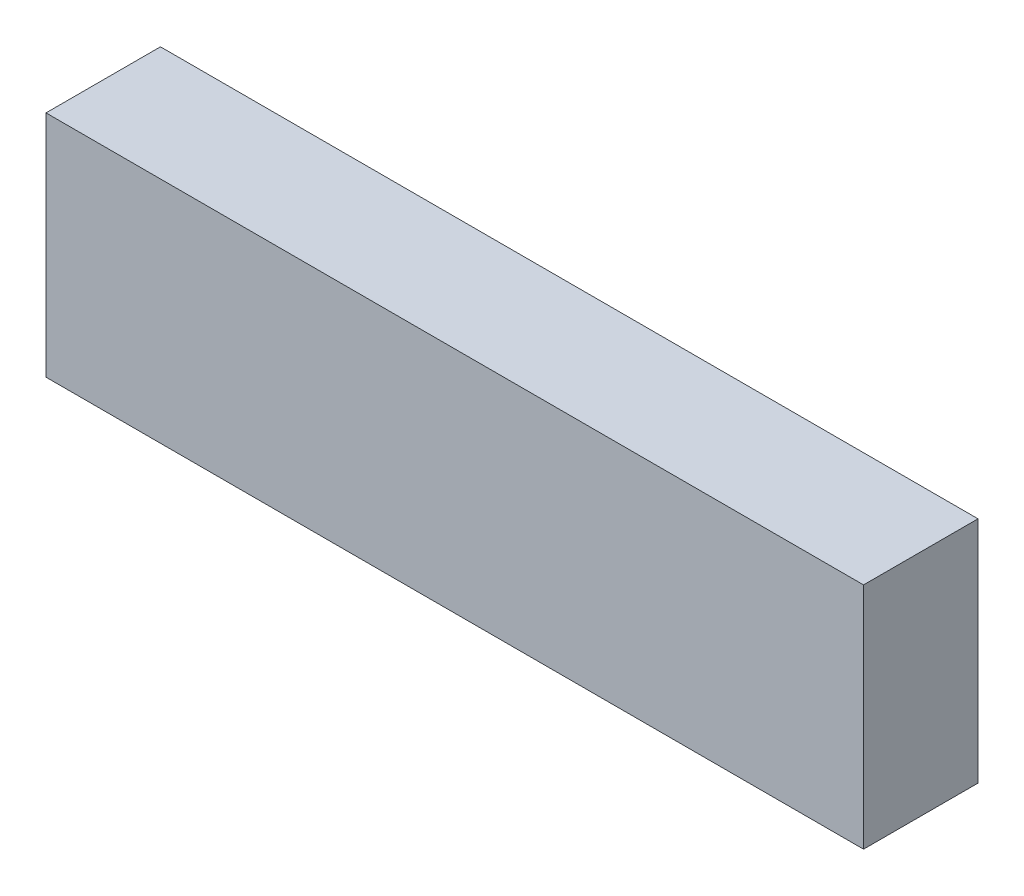
SolidWorks part; units mm, degrees
ref_plane "Plan de face" through (0, 0, 0) normal (0, 0, 1) x (1, 0, 0)
ref_plane "Plan de dessus" through (0, 0, 0) normal (0, 1, 0) x (1, 0, 0)
ref_plane "Plan de droite" through (0, 0, 0) normal (1, 0, 0) x (0, 0, -1)
sketch "Esquisse1" plane through (0, 0, 0) normal (0, 1, 0) x (1, 0, 0)
  line L1 (-125, 17.5) -> (125, 17.5)
  line L2 (-125, 17.5) -> (-125, -17.5)
  line L3 (-125, -17.5) -> (125, -17.5)
  line L4 (125, 17.5) -> (125, -17.5)
  line L5 (-125, 17.5) -> (125, -17.5) construction
  line L6 (-125, -17.5) -> (125, 17.5) construction
  point P0 (0, 0)
  dimension "D1" = 35
  dimension "D2" = 250
extrude "Boss.-Extru.1" add sketch "Esquisse1" along normal blind 70
